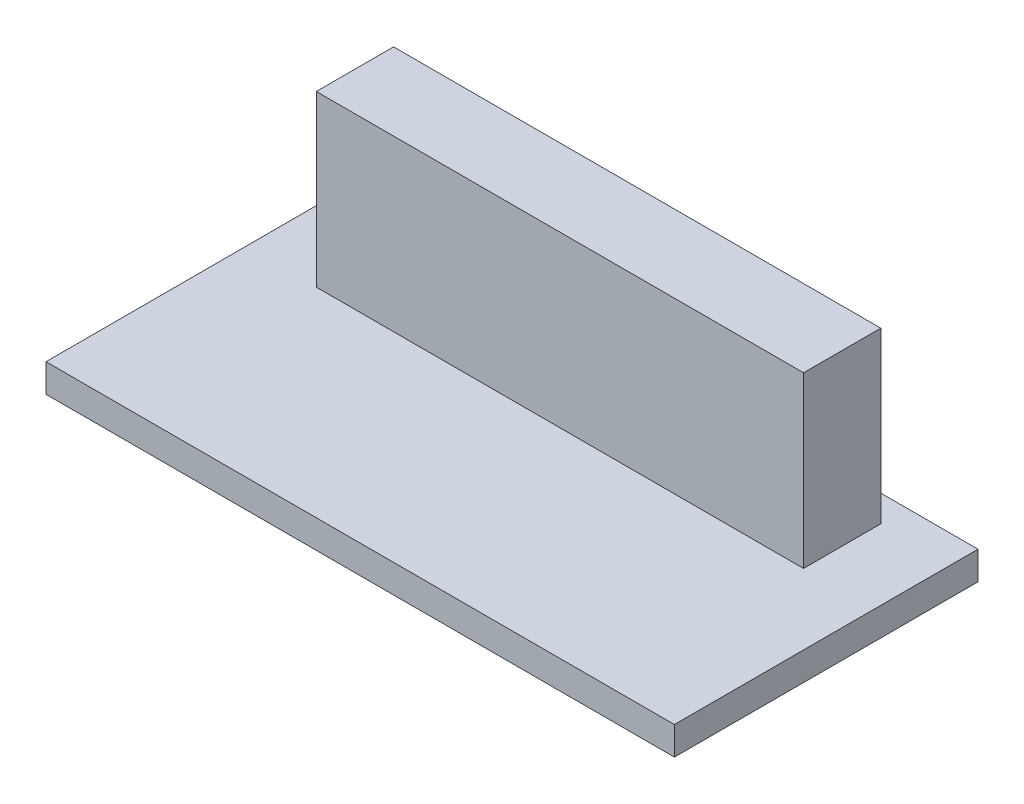
SolidWorks part; units mm, degrees
ref_plane "Front Plane" through (0, 0, 0) normal (0, 0, 1) x (1, 0, 0)
ref_plane "Top Plane" through (0, 0, 0) normal (0, 1, 0) x (1, 0, 0)
ref_plane "Right Plane" through (0, 0, 0) normal (1, 0, 0) x (0, 0, -1)
sketch "Sketch1" plane through (0, 0, 0) normal (0, 1, 0) x (1, 0, 0)
  line L1 (-22.25, -10.75) -> (22.25, -10.75)
  line L2 (-22.25, -10.75) -> (-22.25, 10.75)
  line L3 (-22.25, 10.75) -> (22.25, 10.75)
  line L4 (22.25, -10.75) -> (22.25, 10.75)
  line L5 (-22.25, -10.75) -> (22.25, 10.75) construction
  line L6 (-22.25, 10.75) -> (22.25, -10.75) construction
  point P0 (0, 0)
  dimension "D1" = 44.5
  dimension "D2" = 21.5
extrude "Boss-Extrude1" add sketch "Sketch1" along normal blind 2
sketch "Sketch2" plane through (0, 2, 0) normal (0, 1, 0) x (1, 0, 0)
  line L1 (-17.2506, 8.8653) -> (17.2506, 8.8653)
  line L2 (-17.2506, 8.8653) -> (-17.2506, 3.3947)
  line L3 (-17.2506, 3.3947) -> (17.2506, 3.3947)
  line L4 (17.2506, 8.8653) -> (17.2506, 3.3947)
  line L5 (-17.2506, 8.8653) -> (17.2506, 3.3947) construction
  line L6 (-17.2506, 3.3947) -> (17.2506, 8.8653) construction
  point P0 (0, 6.13)
extrude "Boss-Extrude2" add sketch "Sketch2" along normal blind 12
